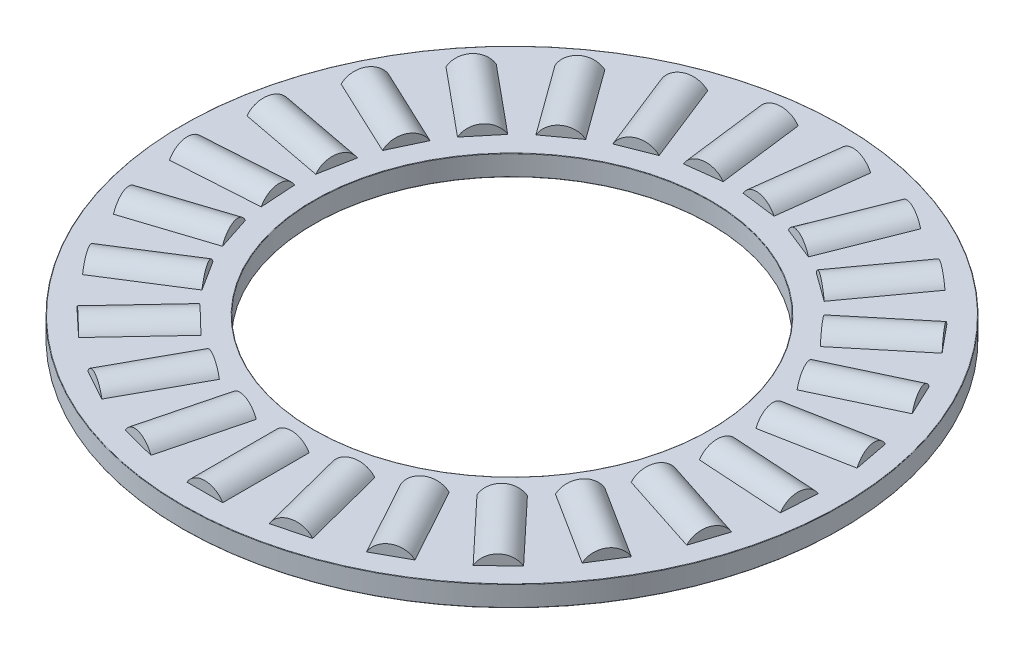
SolidWorks part; units mm, degrees
ref_plane "Front Plane" through (0, 0, 0) normal (0, 0, 1) x (1, 0, 0)
ref_plane "Top Plane" through (0, 0, 0) normal (0, 1, 0) x (1, 0, 0)
ref_plane "Right Plane" through (0, 0, 0) normal (1, 0, 0) x (0, 0, -1)
sketch "Sketch1" plane through (0, 0, 0) normal (1, 0, 0) x (0, 0, -1)
  line L0 (-15.875, 0) -> (15.875, 0) construction
  line L1 (0, -0.9922) -> (0, 0.9922) construction
  line L2 (-15.875, 0.4961) -> (-9.5504, 0.4961)
  line L3 (-15.875, 0.4961) -> (-15.875, -0.4961)
  line L4 (-15.875, -0.4961) -> (-9.5504, -0.4961)
  line L5 (-9.5504, 0.4961) -> (-9.5504, -0.4961)
  line L7 (-12.7127, 0.9922) -> (-12.7127, 0.4961) construction
  line L8 (-14.7963, 0.9922) -> (-10.6291, 0.9922) construction
  line L9 (-14.7963, 0.9922) -> (-14.7963, -0.9922) construction
  line L10 (-14.7963, -0.9922) -> (-10.6291, -0.9922) construction
  line L11 (-10.6291, 0.9922) -> (-10.6291, -0.9922) construction
  point P16 (-14.7963, 0)
  dimension "OD" = 31.75
  dimension "Shaft Dia" = 19.1008
  dimension "Th" = 1.9844
  dimension "D2" = 0.9922
  dimension "D1" = 4.1672
  dimension "D3" = 6.3246
revolve "Revolve1" add sketch "Sketch1" angle 360 about L1
sketch "Sketch3" plane through (0, 0, 0) normal (1, 0, 0) x (0, 0, -1)
  line L0 (-14.7963, 0.9922) -> (-14.7963, -0.9922) construction
  line L1 (-14.7963, 0) -> (-10.6291, 0)
  line L2 (-14.7963, 0) -> (-14.7963, 0.9922)
  line L3 (-14.7963, 0.9922) -> (-10.6291, 0.9922)
  line L4 (-10.6291, 0) -> (-10.6291, 0.9922)
revolve "Cut-Revolve1" cut sketch "Sketch3" angle 360 about L1
sketch "Sketch2" plane through (0, 0, 0) normal (1, 0, 0) x (0, 0, -1)
  line L1 (-14.7963, 0) -> (-10.6291, 0)
  line L2 (-14.7963, 0) -> (-14.7963, 0.9922)
  line L3 (-14.7963, 0.9922) -> (-10.6291, 0.9922)
  line L4 (-10.6291, 0) -> (-10.6291, 0.9922)
revolve "Revolve2" add sketch "Sketch2" angle 360 about L1
ref_axis "Axis1" through (0, 0.9922, 0) along (0, -1, 0)
pattern_circular "CirPattern1" count 25 every 14.4 about axis through (0, 0.9922, 0) along (0, -1, 0) of bodies 187 411
pattern_circular "CirPattern2" count 25 every 14.4 about axis through (0, 0, 0) along (0, 1, 0) of "Cut-Revolve1"
sketch "Sketch4" plane through (0, 0, 0) normal (1, 0, 0) x (0, 0, -1)
  line L0 (-15.875, 0.4961) -> (-15.875, -0.4961) construction
  line L1 (-11.9062, 9.1091) -> (-6.35, 9.1091)
  line L2 (-11.9062, 9.1091) -> (-11.9062, 9.9219)
  line L3 (-11.9062, 9.9219) -> (-6.35, 9.9219)
  line L4 (-6.35, 9.1091) -> (-6.35, 9.9219)
  line L5 (-11.9062, -9.9219) -> (-9.5504, -9.9219)
  line L6 (-11.9062, -9.9219) -> (-11.9062, -9.1091)
  line L7 (-11.9062, -9.1091) -> (-9.5504, -9.1091)
  line L8 (-9.5504, -9.9219) -> (-9.5504, -9.1091)
  line L10 (-9.5504, 0.4961) -> (-9.5504, -0.4961) construction
  line L11 (0, 0) -> (-15.875, 0) construction
  line L12 (-15.875, 0) -> (15.875, 0) construction
  line L13 (0, -0.9922) -> (0, 0.9922) construction
  dimension "Ht" = 19.8438
  dimension "Washer Th" = 0.8128
  dimension "Washer ID" = 12.7
  dimension "Washer OD" = 23.8125
fillet "Fillet2" radius 0.0198 4 edges at (0, -0.4961, -9.5504) (0, 0.4961, -9.5504) (0, -0.4961, -15.875) (0, 0.4961, -15.875)
equation "\"D2@Sketch1\"= \"Th@Sketch1\" * .5"
equation "\"Rollers@CirPattern1\"= \"OD@Sketch1\" * 20"
equation "\"Angle@CirPattern1\" = 360/\"Rollers@CirPattern1\""
equation "\"D1@CirPattern2\" = \"Rollers@CirPattern1\""
equation "\"D2@CirPattern2\" = \"Angle@CirPattern1\""
equation "\"Ht@Sketch4\" = \"Th@Sketch1\"*10"
